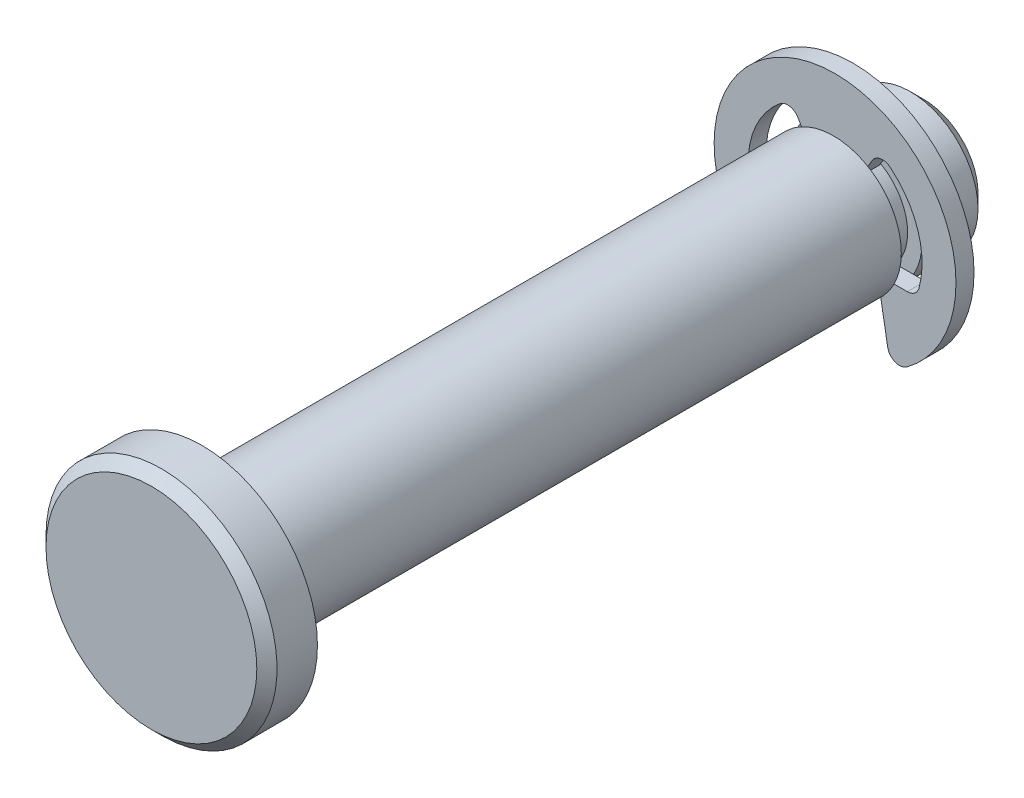
SolidWorks part; units mm, degrees
material "Plain Carbon Steel"
ref_plane "Front" through (0, 0, 0) normal (0, 0, 1) x (1, 0, 0)
ref_plane "Top" through (0, 0, 0) normal (0, 1, 0) x (1, 0, 0)
ref_plane "Right" through (0, 0, 0) normal (1, 0, 0) x (0, 0, -1)
sketch "Sketch2" plane through (0, 0, 0) normal (0, 0, 1) x (1, 0, 0)
  circle A0 centre (0, 0) radius 2.3813
  point P3 (0, 2.3813)
  point P4 (0, -2.3813)
  dimension "dia" = 4.7625
extrude "Extrude1" add sketch "Sketch2" along normal mid plane 25.4
sketch "Sketch3" plane through (0, 0, 0) normal (1, 0, 0) x (0, 0, -1)
  line L0 (12.7, 2.3813) -> (-12.7, 2.3813) construction
  line L1 (9.525, 2.3812) -> (10.2616, 2.3813)
  line L2 (9.525, 2.3812) -> (9.525, 1.8669)
  line L3 (9.525, 1.8669) -> (10.2616, 1.8669)
  line L4 (10.2616, 2.3813) -> (10.2616, 1.8669)
  line L5 (-12.7, 2.3813) -> (-12.7, -2.3813) construction
  line L10 (10.2616, 1.8669) -> (10.2616, -1.8669) construction
  point P11 (10.2616, 0)
  point P14 (9.8933, 2.3813)
  dimension "groove wd" = 0.7366
  dimension "groove dia" = 3.7338
  dimension "usable lg" = 22.225
revolve "Cut-Revolve1" cut sketch "Sketch3" angle 360 about axis through (0, 0, 12.7) along (0, 0, -1)
sketch "Sketch8" plane through (0, 0, 12.7) normal (0, 0, 1) x (1, 0, 0)
  circle A0 centre (0, 0) radius 4.064
  dimension "head dia" = 8.128
extrude "Extrude6" add sketch "Sketch8" along normal blind 1.778
chamfer "Chamfer2" distance 0.3556 angle 45 1 edges at (4.064, 0, 14.478)
ref_plane "Plane1" through (0, 0, -9.8933) normal (0, 0, 1) x (1, 0, 0)
sketch "Sketch4" plane through (0, 0, -9.8933) normal (0, 0, 1) x (1, 0, 0)
  line L0 (0, 1.8669) -> (0, -1.8669) construction
  circle A0 centre (0, 0) radius 4.2545
  circle A1 centre (0, 0) radius 1.8669
  dimension "ring dia" = 8.509
extrude "Extrude2" add sketch "Sketch4" along normal mid plane 0.635 separate body
sketch "Sketch5" plane through (0, 0, 0) normal (0, 0, 1) x (1, 0, 0)
  line L0 (0, 4.2545) -> (0, 1.8669) construction
  line L1 (-1.5304, 2.6506) -> (0, 0)
  line L2 (-2.8484, -1.1201) -> (-1.4935, -1.1201)
  line L3 (0, 0) -> (1.5304, 2.6506)
  line L4 (-1.4935, -1.1201) -> (-1.9617, -3.7753)
  line L5 (1.4935, -1.1201) -> (1.9617, -3.7753)
  line L6 (1.4935, -1.1201) -> (2.8484, -1.1201)
  arc A0 (-1.5304, 2.6506) -> (-2.8484, -1.1201) centre (0, 0) ccw
  circle A1 centre (0, 0) radius 4.2545 construction
  circle A2 centre (0, 0) radius 1.8669 construction
  arc A3 (2.8484, -1.1201) -> (1.5304, 2.6506) centre (0, 0) ccw
  arc A4 (-1.9617, -3.7753) -> (1.9617, -3.7753) centre (0, 0) ccw
  circle A5 centre (0, 0) radius 1.8669 construction
  point P10 (0, 3.0607)
  dimension "D1" = 30
  dimension "D2" = 10
  dimension "D3" = 1.1201
extrude "Extrude4" cut sketch "Sketch5" against normal through all
sketch "Sketch6" plane through (0, 0, -9.5758) normal (0, 0, 1) x (1, 0, 0)
  line L0 (-0.9335, 1.6168) -> (0.9335, 1.6168)
  circle A0 centre (0, 0) radius 1.8669 construction
  arc A1 (0.9335, 1.6168) -> (-0.9335, 1.6168) centre (0, 0) ccw
extrude "Extrude5" add sketch "Sketch6" against normal up to surface (0.635 mm away) up to face at (0, 0.5273, -10.2108)
fillet "Fillet1" radius 0.4254 6 edges at (1.9617, -3.7753, -9.8933) (-1.9617, -3.7753, -9.8933) (2.8484, -1.1201, -9.8933) (1.5304, 2.6506, -9.8933) (-1.5304, 2.6506, -9.8933) (-2.8484, -1.1201, -9.8933)
chamfer "Chamfer1" distance 0.4763 angle 45 1 edges at (2.3813, 0, -12.7)
sketch "Sketch7" plane through (0, 0, 0) normal (1, 0, 0) x (0, 0, -1)
  line L0 (10.2108, 4.2545) -> (9.5758, 4.2545) construction
  line L1 (12.7, -2.3813) -> (12.7, 2.3813) construction
  line L2 (9.5758, -3.5079) -> (10.2108, -3.5079) construction
  line L3 (-14.478, 3.7084) -> (-14.478, -3.7084) construction
  point P0 (10.2616, -3.5079)
  point P1 (12.7, 2.3813)
  point P2 (-14.478, 4.064)
  point P6 (9.525, 4.2545)
  point P7 (12.7, -2.3813)
  point P12 (-12.7, 4.064)
  point P16 (9.525, -3.5079)
equation "\"D1@Chamfer1\" = \"dia@Sketch2\" * .1"
equation "\"D1@Fillet1\" = \"ring dia@Sketch4\" * .05"
equation "\"D3@Sketch5\" = \"groove dia@Sketch3\" * .3"
equation "\"D1@Chamfer2\" = \"head ht@Extrude6\" * .2"
